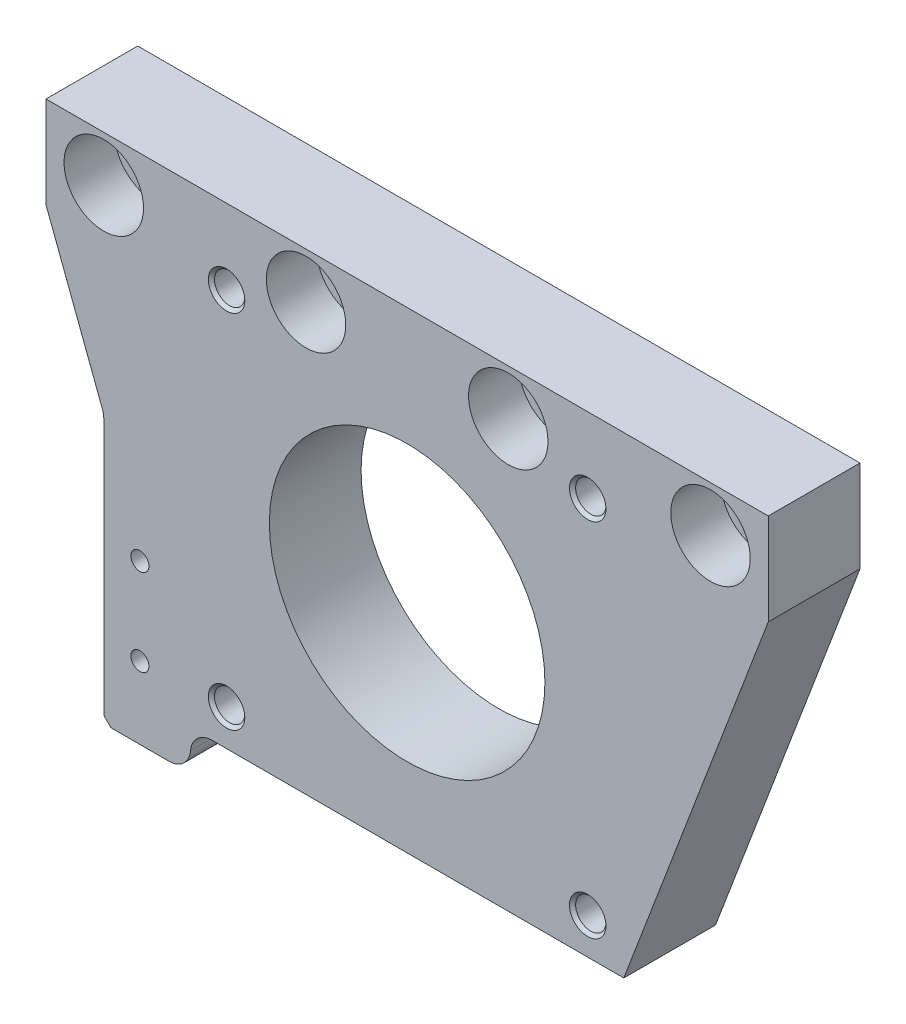
SolidWorks part; units mm, degrees
other "DetailItem2"
other "DetailItem3"
other "DetailItem4"
ref_plane "Front Plane" through (0, 0, 0) normal (0, 0, 1) x (1, 0, 0)
ref_plane "Top Plane" through (0, 0, 0) normal (0, 1, 0) x (1, 0, 0)
ref_plane "Right Plane" through (0, 0, 0) normal (1, 0, 0) x (0, 0, -1)
sketch "Sketch2" plane through (0, 0, 0) normal (0, 0, 1) x (1, 0, 0)
  line B0 (28.2, -28.2) -> (-28.2, -28.2) construction
  line B1 (28.2, -28.2) -> (28.2, 28.2) construction
  line B2 (28.2, 28.2) -> (-28.2, 28.2) construction
  line B3 (-28.2, -28.2) -> (-28.2, 28.2) construction
  line B4 (0, 28.2) -> (0, -28.2) construction
  line B5 (28.2, 0) -> (-28.2, 0) construction
  circle B6 centre (0, 0) radius 19.05 construction
  circle B7 centre (-23.57, 23.57) radius 2.5 construction
  circle B8 centre (23.57, 23.57) radius 2.5 construction
  circle B9 centre (-23.57, 23.57) radius 2.525
  circle B10 centre (23.57, 23.57) radius 2.525
  circle B11 centre (23.57, -23.57) radius 2.525
  circle B12 centre (-23.57, -23.57) radius 2.525
  circle B13 centre (0, 0) radius 19.075
  line B14 (-30, -30) -> (-30, 30) construction
  line B15 (-30, -30) -> (30, -30) construction
  line B16 (30, -30) -> (30, 30) construction
  line B17 (-30, 30) -> (30, 30) construction
  circle B18 centre (0, 0) radius 18 construction
  circle B19 centre (25, 25) radius 2.5 construction
  circle B20 centre (-25, -25) radius 2.5 construction
  circle B21 centre (0, 0) radius 18.025
  circle B22 centre (25, 25) radius 2.525
  circle B23 centre (25, -25) radius 2.525
  circle B24 centre (-25, -25) radius 2.525
  circle B25 centre (-25, 25) radius 2.525
sketch_block_instance "Block1-3"
sketch_block "Block1" parameters "D2"=5, "D5"=38.1, "D1"=56.4, "D3"=47.14, "D4"=47.14
sketch_block_instance "Block4-1"
sketch_block "Block4" parameters "D2"=5, "D5"=36, "D1"=60, "D3"=50, "D4"=50, "D6"=0.025, "D7"=0.025
sketch_block_instance "Nema34 (Some)-1"
sketch_block "Nema34 (Some)"
sketch "Sketch3" plane through (0, 0, 0) normal (0, 0, 1) x (1, 0, 0)
  line L0 (0, 0) -> (0, 22.7) construction
  line L1 (-50, 22.7) -> (50, 22.7) construction
  line L2 (-50, 35.4) -> (50, 35.4)
  line L3 (-50, 22.7) -> (-30, -30)
  line L5 (-30, -30) -> (30, -30)
  line L6 (30, -30) -> (50, 22.7)
  line L11 (-50, 35.4) -> (-50, 22.7)
  line L15 (50, 22.7) -> (50, 35.4)
  line L16 (-50, 29.05) -> (50, 29.05) construction
  circle A0 centre (0, 0) radius 19.075 construction
  circle A9 centre (0, 0) radius 19.075
  circle A10 centre (-42, 29.05) radius 2.525
  circle A11 centre (42, 29.05) radius 2.525
  circle A12 centre (-14, 29.05) radius 2.525
  circle A14 centre (14, 29.05) radius 2.525
  point P19 (0, 22.7)
  dimension "D1" = 22.7
  dimension "D4" = 5.05
  dimension "D5" = 8
  dimension "D6" = 84
  dimension "D7" = 28
  dimension "D3" = 100
  dimension "D2" = 12.7
extrude "Boss-Extrude1" add sketch "Sketch3" against normal blind 12.7
hole_wizard "M5x0.8 Tapped Hole1" positions "Sketch4" profile "Sketch5" tap size "M5x0.8" standard "ANSI Metric" end condition through all
sketch "Sketch4" plane through (0, 0, 0) normal (0, 0, 1) x (1, 0, 0)
  point P0 (-25, 25)
  point P3 (25, 25)
  point P6 (25, -25)
  point P9 (-25, -25)
sketch "Sketch5" plane through (-25, 25, 0) normal (1, 0, 0) x (0, -1, 0)
  line L0 (0, 0) -> (0, 12.7)
  line L1 (0, 12.7) -> (2.1, 12.7)
  line L2 (2.1, 12.7) -> (2.1, 0.425)
  line L3 (2.1, 0.425) -> (2.525, 0)
  line L5 (2.525, 0) -> (0, 0)
  line L6 (-2.1, 0.425) -> (-2.525, 0) construction
  line L11 (0, -6.35) -> (0, 107.95) construction
  dimension "Thru Tap Drill Dia." = 4.2
  dimension "Thru Tap Drill Depth" = 12.7
  dimension "Near C'Sink Dia." = 5.05
  dimension "Near C'Sink Angle" = 90
cosmetic thread "Hole Thread1" parameters "D2"=5
cosmetic thread "Hole Thread2" parameters "D2"=5
cosmetic thread "Hole Thread3" parameters "D2"=5
cosmetic thread "Hole Thread4" parameters "D2"=5
sketch "Sketch8" plane through (0, 0, 0) normal (0, 0, 1) x (1, 0, 0)
  circle A0 centre (-42, 29.05) radius 5.5
  circle A1 centre (-14, 29.05) radius 5.5
  circle A2 centre (14, 29.05) radius 5.5
  circle A3 centre (42, 29.05) radius 5.5
  dimension "D1" = 11
extrude "Cut-Extrude1" cut sketch "Sketch8" against normal blind 7
sketch "Sketch9" plane through (0, 0, 0) normal (0, 0, 1) x (1, 0, 0)
  line L0 (-30, -30) -> (-30, -35.5)
  line L1 (-30, -35.5) -> (-42, -35.5)
  line L2 (-42, -35.5) -> (-42, 1.62)
  line L3 (-30, -30) -> (-42, 1.62)
  line L4 (-50, 22.7) -> (-30, -30) construction
  line L5 (-30, -30) -> (30, -30) construction
  dimension "D1" = 5.5
  dimension "D2" = 12
extrude "Boss-Extrude2" add sketch "Sketch9" against normal up to surface (12.7 mm away) up to face at (-22.9, 25, -12.7)
sketch "Sketch10" plane through (-42, 0, 0) normal (-1, 0, 0) x (0, 0, 1)
  line L0 (-12.7, -35.5) -> (-12.7, 1.62) construction
  line L2 (-12.7, -35.5) -> (0, -35.5) construction
  line B0 (4.55, -33.25) -> (6.05, -33.25) construction
  line B1 (6.05, -29.75) -> (4.55, -29.75) construction
  line B2 (4.55, -21.25) -> (6.05, -21.25) construction
  line B3 (6.05, -17.75) -> (4.55, -17.75) construction
  line B4 (-20.7, -16.6) -> (-20.7, -34.4) construction
  line B5 (-20.6, -34.5) -> (9.7, -34.5) construction
  line B6 (9.8, -34.4) -> (9.8, -16.6) construction
  line B7 (9.7, -16.5) -> (-20.6, -16.5) construction
  arc B8 (6.05, -33.25) -> (6.05, -29.75) centre (6.05, -31.5) ccw construction
  arc B9 (4.55, -29.75) -> (4.55, -33.25) centre (4.55, -31.5) ccw construction
  arc B10 (4.55, -17.75) -> (4.55, -21.25) centre (4.55, -19.5) ccw construction
  arc B11 (6.05, -21.25) -> (6.05, -17.75) centre (6.05, -19.5) ccw construction
  circle B12 centre (-12.7, -25.5) radius 6 construction
  arc B13 (-20.7, -34.4) -> (-20.6, -34.5) centre (-20.6, -34.4) ccw construction
  arc B14 (9.7, -34.5) -> (9.8, -34.4) centre (9.7, -34.4) ccw construction
  arc B15 (9.8, -16.6) -> (9.7, -16.5) centre (9.7, -16.6) ccw construction
  arc B16 (-20.6, -16.5) -> (-20.7, -16.6) centre (-20.6, -16.6) ccw construction
  dimension "D1" = 1
  dimension "D2" = 8
sketch_block_instance "Block5-1"
sketch_block "Block5"
fillet "Fillet1" radius 3 2 edges at (-30, -30, -6.35) (-42, 1.62, -6.35)
fillet "Fillet2" radius 3 1 edges at (-30, -35.5, -6.35)
chamfer "Chamfer1" distance 1 angle 45 1 edges at (-42, -35.5, -6.35)
sketch "Sketch13" plane through (0, 0, 0) normal (0, 0, 1) x (1, 0, 0)
  line L0 (-42, -13.5) -> (-37, -13.5) construction
  line L1 (-42, 1.0699) -> (-42, -34.5) construction
  line L2 (-42, -19.5) -> (-42, -31.5) construction
  line L3 (-42, -25.5) -> (-37, -25.5) construction
  line L4 (-42, -19.5) -> (-42, -31.5) construction
  line L5 (-42, -19.5) -> (-42, -31.5) construction
  line L6 (-42, -25.5) -> (-37, -25.5) construction
  point P21 (-37, -25.5)
  dimension "D1" = 5
  dimension "D2" = 12
hole_wizard "M3x0.5 Tapped Hole2" positions "Sketch14" profile "Sketch16" tap size "M3x0.5" standard "ANSI Metric" end condition through all
sketch "Sketch14" plane through (0, 0, 0) normal (0, 0, 1) x (1, 0, 0)
  point P0 (-37, -13.5)
  point P3 (-37, -25.5)
sketch "Sketch16" plane through (-37, -13.5, 0) normal (1, 0, 0) x (0, -1, 0)
  line L0 (0, 0) -> (0, 12.7)
  line L1 (0, 12.7) -> (1.25, 12.7)
  line L2 (1.25, 12.7) -> (1.25, 0)
  line L5 (1.25, 0) -> (0, 0)
  line L11 (0, -6.35) -> (0, 107.95) construction
  dimension "Thru Tap Drill Dia." = 2.5
  dimension "Thru Tap Drill Depth" = 12.7
cosmetic thread "Hole Thread7" parameters "D2"=3
cosmetic thread "Hole Thread8" parameters "D2"=3
equation "\"D3\"= \"D4\""
equation "\"D3@Nema34 (Some)\"=\"D4@Nema34 (Some)\""
